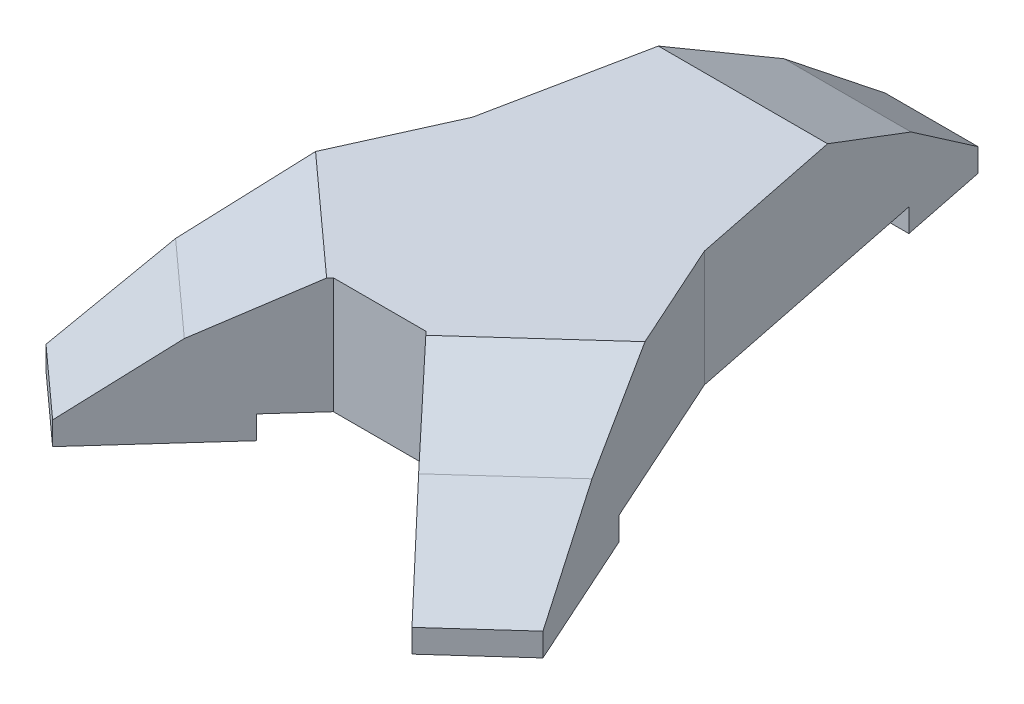
SolidWorks part; units mm, degrees
ref_plane "Front Plane" through (0, 0, 0) normal (0, 0, 1) x (1, 0, 0)
ref_plane "Top Plane" through (0, 0, 0) normal (0, 1, 0) x (1, 0, 0)
ref_plane "Right Plane" through (0, 0, 0) normal (1, 0, 0) x (0, 0, -1)
sketch "Sketch1" plane through (0, 0, 0) normal (0, 1, 0) x (1, 0, 0)
  line L0 (0, 28.8124) -> (0, 104.0803) construction
  line L1 (0, 95.8147) -> (-12.7, 95.8147)
  line L2 (-12.7, 95.8147) -> (-31.75, 1.8347)
  line L3 (-31.75, 1.8347) -> (-68.0487, -78.6719)
  line L4 (-68.0487, -78.6719) -> (-49.2052, -95.7037)
  line L5 (-49.2052, -95.7037) -> (-12.7, -55.3153)
  line L6 (-12.7, -55.3153) -> (0, -55.3153)
  line L7 (-31.75, 1.8347) -> (-49.2052, -95.7037) construction
  line L8 (-68.0487, -78.6719) -> (-12.7, -55.3153) construction
  line L9 (0, 67.8747) -> (-31.75, 1.8347) construction
  line L10 (-31.75, 1.8347) -> (-12.7, -55.3153) construction
  line L11 (-31.75, 1.8347) -> (0, 1.8347) construction
  line L12 (0, 95.8147) -> (0, -55.3153)
  point P13 (0, -17.2427)
  dimension "D1" = 12.7
  dimension "D2" = 93.98
  dimension "D3" = 25.4
  dimension "D4" = 12.7
  dimension "D5" = 27.94
  dimension "D6" = 57.15
  dimension "D7" = 31.75
extrude "Boss-Extrude1" add sketch "Sketch1" along normal blind 6.35
sketch "Sketch3" plane through (20.5272, 0, 18.5535) normal (0.7419, 0, 0.6705) x (0.6705, 0, -0.7419)
  line L0 (-103.994, 6.35) -> (-78.4532, 24.7336)
  line L1 (-78.4532, 24.7336) -> (-50.8647, 38.1)
  line L2 (-50.8647, 38.1) -> (9.6296, 38.1)
  line L3 (9.6296, 38.1) -> (9.6296, 6.35)
  line L4 (9.6296, 6.35) -> (-103.994, 6.35)
  line L5 (-41.0368, 6.35) -> (71.0822, 6.35) construction
  dimension "D1" = 31.75
extrude "Boss-Extrude2" add sketch "Sketch3" against normal up to surface (61.9666 mm away)
sketch "Sketch4" plane through (0, 0, -3.1586) normal (-1, 0, 0) x (0, 0, 1)
  line L0 (-92.6561, 6.35) -> (1.3239, 6.35)
  line L1 (1.3239, 6.35) -> (1.3239, 38.1)
  line L2 (1.3239, 38.1) -> (-40.9922, 38.1)
  line L3 (-40.9922, 38.1) -> (-69.6317, 23.6735)
  line L4 (-69.6317, 23.6735) -> (-92.6561, 6.35)
  dimension "D1" = 31.75
extrude "Boss-Extrude4" add sketch "Sketch4" along normal up to surface (23.1724 mm away)
sketch "Sketch5" plane through (0, 6.35, 0) normal (0, 1, 0) x (1, 0, 0)
  line L0 (0, -41.2643) -> (0, -55.3153)
  line L1 (0, -55.3153) -> (-12.7, -55.3153)
  line L2 (-12.7, -55.3153) -> (0, -41.2643)
extrude "Boss-Extrude5" add sketch "Sketch5" along normal up to surface (31.75 mm away) up to face at (-12.3751, 38.1, -1.0895)
sketch "Sketch6" plane through (0, 38.1, 0) normal (0, 1, 0) x (1, 0, 0)
  line L0 (0, -55.3153) -> (0, -41.2643) construction
  line L5 (0, -45.4274) -> (35.3984, -45.4274)
  line L6 (0, -45.4274) -> (0, 18.0141)
  line L7 (0, 18.0141) -> (35.3984, 18.0141)
  line L8 (35.3984, -45.4274) -> (35.3984, 18.0141)
extrude "Cut-Extrude3" cut sketch "Sketch6" against normal through all
sketch "Sketch7" plane through (0, 0, 0) normal (0, -1, 0) x (1, 0, 0)
  line L0 (-22.701, 66.3802) -> (-50.9815, 40.8188)
  line L1 (-49.2052, 95.7037) -> (-12.7, 55.3153) construction
  line L2 (-31.75, -1.8347) -> (-68.0487, 78.6719) construction
  line L3 (-50.9815, 40.8188) -> (-31.75, -1.8347)
  line L4 (-31.75, -1.8347) -> (-17.5138, -72.0667)
  line L5 (-12.7, -95.8147) -> (-31.75, -1.8347) construction
  line L6 (-17.5138, -72.0667) -> (0, -72.0667)
  line L7 (0, 55.3153) -> (0, -95.8147) construction
  line L8 (0, -72.0667) -> (0, 55.3153)
  line L9 (0, 55.3153) -> (-12.7, 55.3153)
  line L10 (-12.7, 55.3153) -> (-22.701, 66.3802)
extrude "Cut-Extrude2" cut sketch "Sketch7" against normal blind 6.35
mirror "Mirror2" about plane through (0, 0, 0) normal (1, 0, 0) of bodies 107
sketch "Sketch8" plane through (0, 38.1, 0) normal (0, 1, 0) x (-1, 0, 0)
  circle A0 centre (0, 13.8524) radius 20.0563 construction
